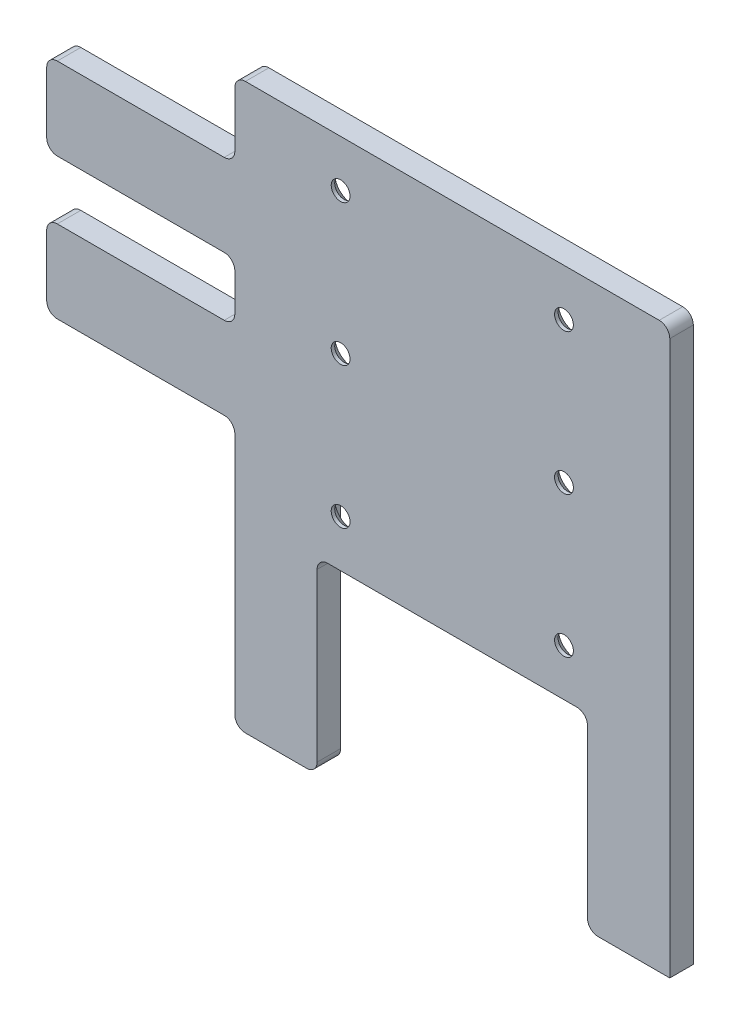
SolidWorks part; units mm, degrees
ref_plane "前视基准面" through (0, 0, 0) normal (0, 0, 1) x (1, 0, 0)
ref_plane "上视基准面" through (0, 0, 0) normal (0, 1, 0) x (1, 0, 0)
ref_plane "右视基准面" through (0, 0, 0) normal (1, 0, 0) x (0, 0, -1)
sketch "草图1" plane through (0, 0, 0) normal (0, 0, 1) x (1, 0, 0)
  line L1 (-18, 56) -> (56, 56)
  line L2 (-18, 56) -> (-18, -8)
  line L3 (-18, -8) -> (56, -8)
  line L4 (56, 56) -> (56, -8)
  line L5 (-18, -8) -> (-4, -8)
  line L6 (-18, -8) -> (-18, -40)
  line L7 (-18, -40) -> (-4, -40)
  line L8 (-4, -8) -> (-4, -40)
  line L9 (56, -8) -> (42, -8)
  line L10 (56, -8) -> (56, -40)
  line L11 (56, -40) -> (42, -40)
  line L12 (42, -8) -> (42, -40)
  line L13 (-18, 43) -> (-50, 43)
  line L14 (-18, 43) -> (-18, 29)
  line L15 (-18, 29) -> (-50, 29)
  line L16 (-50, 43) -> (-50, 29)
  line L17 (-18, 19) -> (-50, 19)
  line L18 (-18, 19) -> (-18, 5)
  line L19 (-18, 5) -> (-50, 5)
  line L20 (-50, 19) -> (-50, 5)
  circle A0 centre (0, 0) radius 1.6
  circle A1 centre (38, 0) radius 1.6
  circle A2 centre (38, 24) radius 1.6
  circle A3 centre (38, 48) radius 1.6
  circle A4 centre (0, 24) radius 1.6
  circle A5 centre (0, 48) radius 1.6
  point P31 (-50, 36)
  point P32 (-50, 12)
  dimension "D1" = 3.2
  dimension "D4" = 8
  dimension "D5" = 8
  dimension "D6" = 18
  dimension "D7" = 18
  dimension "D16" = 12
  dimension "D8" = 14
  dimension "D9" = 32
  dimension "D10" = 32
  dimension "D11" = 14
  dimension "D12" = 32
  dimension "D13" = 32
  dimension "D14" = 14
  dimension "D15" = 14
  dimension "D17" = 12
  dimension "D2" = 2
  dimension "D3" = 3
extrude "凸台-拉伸1" add sketch "草图1" along normal blind 2 contours L17 L20 L19 L2 | L13 L16 L15 L2 | L4 L1 L2 L3 A5 A4 A3 A2 A1 A0 | L8 L3 L6 L7 | L3 L12 L11 L10
chamfer "倒角1" distance 1.4 angle 45 6 edges at (39.6, 48, 0) (1.6, 48, 0) (39.6, 24, 0) (1.6, 24, 0) (39.6, 0, 0) (1.6, 0, 0)
sketch "草图2" plane through (0, 0, 0) normal (0, 0, -1) x (-1, 0, 0)
  line L0 (-56, 56) -> (-56, -40) construction
  line L1 (50, 43) -> (-56, 43)
  line L2 (50, 43) -> (50, 41.2)
  line L3 (50, 41.2) -> (-56, 41.2)
  line L4 (-56, 43) -> (-56, 41.2)
  line L5 (18, 56) -> (-56, 56) construction
  line L6 (50, 29) -> (-56, 29)
  line L7 (50, 29) -> (50, 30.8)
  line L8 (50, 30.8) -> (-56, 30.8)
  line L9 (-56, 29) -> (-56, 30.8)
  line L10 (50, 19) -> (-56, 19)
  line L11 (50, 19) -> (50, 17.2)
  line L12 (50, 17.2) -> (-56, 17.2)
  line L13 (-56, 19) -> (-56, 17.2)
  line L14 (50, 5) -> (-56, 5)
  line L15 (50, 5) -> (50, 6.8)
  line L16 (50, 6.8) -> (-56, 6.8)
  line L17 (-56, 5) -> (-56, 6.8)
  line L18 (-56, -40) -> (-54.2, -40)
  line L19 (-56, -40) -> (-56, 56)
  line L20 (-56, 56) -> (-54.2, 56)
  line L21 (-54.2, -40) -> (-54.2, 56)
  line L22 (18, 56) -> (18, 43) construction
  line L23 (-42, -40) -> (-43.8, -40)
  line L24 (-42, -40) -> (-42, 5)
  line L25 (-42, 5) -> (-43.8, 5)
  line L26 (-43.8, -40) -> (-43.8, 5)
  line L27 (4, -40) -> (5.8, -40)
  line L28 (4, -40) -> (4, 5)
  line L29 (4, 5) -> (5.8, 5)
  line L30 (5.8, -40) -> (5.8, 5)
  line L31 (18, -40) -> (16.2, -40)
  line L32 (18, -40) -> (18, 5)
  line L33 (18, 5) -> (16.2, 5)
  line L34 (16.2, -40) -> (16.2, 5)
  line L35 (-54.2, 56) -> (18, 56)
  line L36 (-54.2, 56) -> (-54.2, 54.2)
  line L37 (-54.2, 54.2) -> (18, 54.2)
  line L38 (18, 56) -> (18, 54.2)
  line L39 (18, 29) -> (18, 19) construction
  line L40 (18, 43) -> (16.2, 43)
  line L41 (18, 43) -> (18, 54.2)
  line L42 (18, 54.2) -> (16.2, 54.2)
  line L43 (16.2, 43) -> (16.2, 54.2)
  line L44 (50, 41.2) -> (48.2, 41.2)
  line L45 (50, 41.2) -> (50, 30.8)
  line L46 (50, 30.8) -> (48.2, 30.8)
  line L47 (48.2, 41.2) -> (48.2, 30.8)
  line L48 (50, 17.2) -> (48.2, 17.2)
  line L49 (50, 17.2) -> (50, 6.8)
  line L50 (50, 6.8) -> (48.2, 6.8)
  line L51 (48.2, 17.2) -> (48.2, 6.8)
  line L52 (-54.2, -40) -> (-43.8, -40)
  line L53 (-54.2, -40) -> (-54.2, -38.2)
  line L54 (-54.2, -38.2) -> (-43.8, -38.2)
  line L55 (-43.8, -40) -> (-43.8, -38.2)
  line L56 (5.8, -40) -> (16.2, -40)
  line L57 (5.8, -40) -> (5.8, -38.2)
  line L58 (5.8, -38.2) -> (16.2, -38.2)
  line L59 (16.2, -40) -> (16.2, -38.2)
  line L60 (18, 29) -> (16.2, 29)
  line L61 (18, 29) -> (18, 19)
  line L62 (18, 19) -> (16.2, 19)
  line L63 (16.2, 29) -> (16.2, 19)
  line M21 (18, 19) -> (18, 29)
  line M23 (50, 29) -> (50, 43)
  line M25 (18, 43) -> (18, 56)
  line M26 (18, 56) -> (-56, 56)
  line M27 (-56, 56) -> (-56, -40)
  line M28 (-56, -40) -> (-42, -40)
  line M29 (-42, -40) -> (-42, -8)
  line M31 (4, -8) -> (4, -40)
  line M32 (4, -40) -> (18, -40)
  line M33 (18, -40) -> (18, 5)
  line M35 (50, 5) -> (50, 19)
  dimension "D1" = 1.8
  dimension "D2" = 1.8
  dimension "D3" = 1.8
  dimension "D4" = 1.8
  dimension "D5" = 1.8
extrude "凸台-拉伸2" add sketch "草图2" along normal blind 2 contours L54 L21 L26 M28 | L26 L24 L14 M28 M29 | L21 L14 M28 M27 | L30 L14 L28 M32 M31 | L58 L30 L34 M32 | L34 L14 M32 M33 | L12 L51 L16 M35 | L3 L47 L8 M23 | L6 L63 L10 M21 | L43 L1 L37 M25 | L21 L37 M25 M26 | L1 L21 M26 M27 | L8 L21 L3 M27 | L10 L21 L6 M27 | L16 L21 L12 M27
fillet "圆角1" radius 1.8 15 edges at (-18, 5, 0) (-18, -40, 0) (-4, -40, 0) (-4, -8, 1) (42, -8, 1) (42, -40, 0) (56, 56, 0) (-18, 56, 0) (-18, 43, 0) (-18, 19, 0) (-18, 29, 0) (-50, 5, 0) (-50, 19, 0) (-50, 29, 0) (-50, 43, 0)
